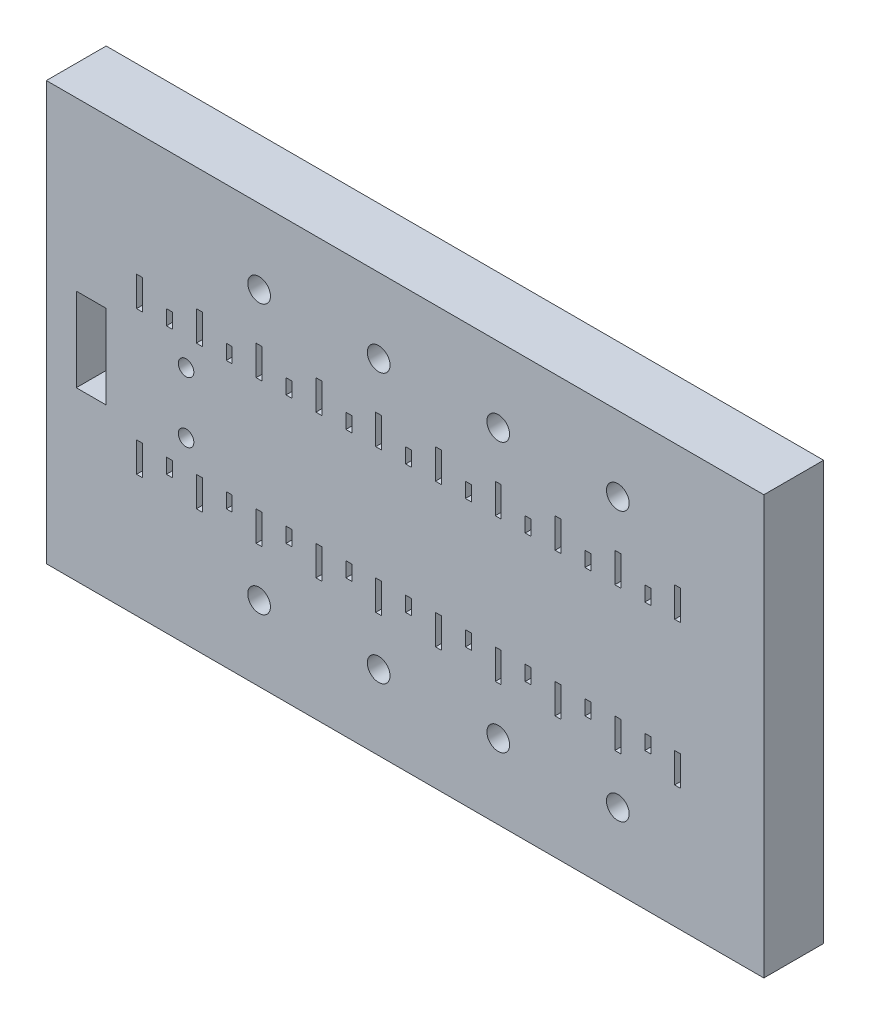
SolidWorks part; units mm, degrees
ref_plane "Front Plane" through (0, 0, 0) normal (0, 0, 1) x (1, 0, 0)
ref_plane "Top Plane" through (0, 0, 0) normal (0, 1, 0) x (1, 0, 0)
ref_plane "Right Plane" through (0, 0, 0) normal (1, 0, 0) x (0, 0, -1)
sketch "Sketch1" plane through (0, 0, 0) normal (0, 0, 1) x (1, 0, 0)
  line L1 (60, -35) -> (-60, -35)
  line L2 (60, -35) -> (60, 35)
  line L3 (60, 35) -> (-60, 35)
  line L4 (-60, -35) -> (-60, 35)
  line L5 (60, -35) -> (-60, 35) construction
  line L6 (60, 35) -> (-60, -35) construction
  point P0 (0, 0)
  dimension "D1" = 120
  dimension "D2" = 70
extrude "Boss-Extrude1" add sketch "Sketch1" along normal blind 10
sketch "Sketch2" plane through (0, 0, 10) normal (0, 0, 1) x (1, 0, 0)
  line L0 (-60, 35) -> (-60, -35)
  line L2 (-60, 0) -> (-52.5, 0)
  line L3 (-55, 7) -> (-50, 7)
  line L4 (-55, 7) -> (-55, -7)
  line L5 (-55, -7) -> (-50, -7)
  line L6 (-50, 7) -> (-50, -7)
  line L7 (-55, 7) -> (-50, -7) construction
  line L8 (-55, -7) -> (-50, 7) construction
  point P3 (-60, 0)
  dimension "D1" = 7.5
  dimension "D2" = 5
  dimension "D3" = 14
extrude "Cut-Extrude1" cut sketch "Sketch2" against normal through all
sketch "Sketch3" plane through (0, 0, 10) normal (0, 0, 1) x (1, 0, 0)
  line L0 (-33.8418, 0) -> (-20.9058, 0)
  line L1 (-33.8418, -8.0899) -> (-33.8418, 8.0899) construction
  circle A0 centre (-36.6358, 5.08) radius 1.3
  circle A1 centre (-36.6358, -5.08) radius 1.3
extrude "Cut-Extrude2" cut sketch "Sketch3" against normal through all contours A0 | A1
sketch "Sketch4" plane through (0, 0, 10) normal (0, 0, 1) x (1, 0, 0)
  line L0 (-34.4209, -2) -> (-34.4209, -12)
  line L1 (-34.4209, -12) -> (-24.4209, -12)
  line L3 (-34.9209, -9.5) -> (-33.9209, -9.5)
  line L4 (-34.9209, -9.5) -> (-34.9209, -14.5)
  line L5 (-34.9209, -14.5) -> (-33.9209, -14.5)
  line L6 (-33.9209, -9.5) -> (-33.9209, -14.5)
  line L7 (-34.9209, -9.5) -> (-33.9209, -14.5) construction
  line L8 (-34.9209, -14.5) -> (-33.9209, -9.5) construction
  line L14 (-29.9127, -12) -> (-28.9127, -12)
  line L15 (-29.4127, -12) -> (-29.4127, -9.5)
  line L17 (-29.9127, -12) -> (-29.9127, -9.5)
  line L18 (-29.9127, -9.5) -> (-28.9127, -9.5)
  line L19 (-28.9127, -12) -> (-28.9127, -9.5)
  line L20 (-29.9127, -12) -> (-28.9127, -9.5) construction
  line L21 (-29.9127, -9.5) -> (-28.9127, -12) construction
  line L22 (-24.9209, -9.5) -> (-24.9209, -14.5)
  line L23 (-24.9209, -14.5) -> (-23.9209, -14.5)
  line L24 (-23.9209, -9.5) -> (-23.9209, -14.5)
  line L25 (-19.9127, -12) -> (-18.9127, -12)
  line L27 (-19.9127, -12) -> (-19.9127, -9.5)
  line L28 (-18.9127, -12) -> (-18.9127, -9.5)
  line L29 (-24.9209, -9.5) -> (-23.9209, -14.5) construction
  line L30 (-24.9209, -14.5) -> (-23.9209, -9.5) construction
  line L31 (-19.9127, -12) -> (-18.9127, -9.5) construction
  line L32 (-19.9127, -9.5) -> (-18.9127, -12) construction
  line L33 (-24.9209, -9.5) -> (-23.9209, -9.5)
  line L34 (-19.9127, -9.5) -> (-18.9127, -9.5)
  line L36 (-14.9209, -9.5) -> (-14.9209, -14.5)
  line L37 (-14.9209, -14.5) -> (-13.9209, -14.5)
  line L38 (-13.9209, -9.5) -> (-13.9209, -14.5)
  line L39 (-9.9127, -12) -> (-8.9127, -12)
  line L41 (-9.9127, -12) -> (-9.9127, -9.5)
  line L42 (-8.9127, -12) -> (-8.9127, -9.5)
  line L43 (-14.9209, -9.5) -> (-13.9209, -14.5) construction
  line L44 (-14.9209, -14.5) -> (-13.9209, -9.5) construction
  line L45 (-9.9127, -12) -> (-8.9127, -9.5) construction
  line L46 (-9.9127, -9.5) -> (-8.9127, -12) construction
  line L47 (-14.9209, -9.5) -> (-13.9209, -9.5)
  line L48 (-9.9127, -9.5) -> (-8.9127, -9.5)
  line L50 (-4.9209, -9.5) -> (-4.9209, -14.5)
  line L51 (-4.9209, -14.5) -> (-3.9209, -14.5)
  line L52 (-3.9209, -9.5) -> (-3.9209, -14.5)
  line L53 (0.0873, -12) -> (1.0873, -12)
  line L55 (0.0873, -12) -> (0.0873, -9.5)
  line L56 (1.0873, -12) -> (1.0873, -9.5)
  line L57 (-4.9209, -9.5) -> (-3.9209, -14.5) construction
  line L58 (-4.9209, -14.5) -> (-3.9209, -9.5) construction
  line L59 (0.0873, -12) -> (1.0873, -9.5) construction
  line L60 (0.0873, -9.5) -> (1.0873, -12) construction
  line L61 (-4.9209, -9.5) -> (-3.9209, -9.5)
  line L62 (0.0873, -9.5) -> (1.0873, -9.5)
  line L64 (5.0791, -9.5) -> (5.0791, -14.5)
  line L65 (5.0791, -14.5) -> (6.0791, -14.5)
  line L66 (6.0791, -9.5) -> (6.0791, -14.5)
  line L67 (10.0873, -12) -> (11.0873, -12)
  line L69 (10.0873, -12) -> (10.0873, -9.5)
  line L70 (11.0873, -12) -> (11.0873, -9.5)
  line L71 (5.0791, -9.5) -> (6.0791, -14.5) construction
  line L72 (5.0791, -14.5) -> (6.0791, -9.5) construction
  line L73 (10.0873, -12) -> (11.0873, -9.5) construction
  line L74 (10.0873, -9.5) -> (11.0873, -12) construction
  line L75 (5.0791, -9.5) -> (6.0791, -9.5)
  line L76 (10.0873, -9.5) -> (11.0873, -9.5)
  line L78 (15.0791, -9.5) -> (15.0791, -14.5)
  line L79 (15.0791, -14.5) -> (16.0791, -14.5)
  line L80 (16.0791, -9.5) -> (16.0791, -14.5)
  line L81 (20.0873, -12) -> (21.0873, -12)
  line L83 (20.0873, -12) -> (20.0873, -9.5)
  line L84 (21.0873, -12) -> (21.0873, -9.5)
  line L85 (15.0791, -9.5) -> (16.0791, -14.5) construction
  line L86 (15.0791, -14.5) -> (16.0791, -9.5) construction
  line L87 (20.0873, -12) -> (21.0873, -9.5) construction
  line L88 (20.0873, -9.5) -> (21.0873, -12) construction
  line L89 (15.0791, -9.5) -> (16.0791, -9.5)
  line L90 (20.0873, -9.5) -> (21.0873, -9.5)
  line L92 (25.0791, -9.5) -> (25.0791, -14.5)
  line L93 (25.0791, -14.5) -> (26.0791, -14.5)
  line L94 (26.0791, -9.5) -> (26.0791, -14.5)
  line L95 (30.0873, -12) -> (31.0873, -12)
  line L97 (30.0873, -12) -> (30.0873, -9.5)
  line L98 (31.0873, -12) -> (31.0873, -9.5)
  line L99 (25.0791, -9.5) -> (26.0791, -14.5) construction
  line L100 (25.0791, -14.5) -> (26.0791, -9.5) construction
  line L101 (30.0873, -12) -> (31.0873, -9.5) construction
  line L102 (30.0873, -9.5) -> (31.0873, -12) construction
  line L103 (25.0791, -9.5) -> (26.0791, -9.5)
  line L104 (30.0873, -9.5) -> (31.0873, -9.5)
  line L106 (35.0791, -9.5) -> (35.0791, -14.5)
  line L107 (35.0791, -14.5) -> (36.0791, -14.5)
  line L108 (36.0791, -9.5) -> (36.0791, -14.5)
  line L109 (40.0873, -12) -> (41.0873, -12)
  line L111 (40.0873, -12) -> (40.0873, -9.5)
  line L112 (41.0873, -12) -> (41.0873, -9.5)
  line L113 (35.0791, -9.5) -> (36.0791, -14.5) construction
  line L114 (35.0791, -14.5) -> (36.0791, -9.5) construction
  line L115 (40.0873, -12) -> (41.0873, -9.5) construction
  line L116 (40.0873, -9.5) -> (41.0873, -12) construction
  line L117 (35.0791, -9.5) -> (36.0791, -9.5)
  line L118 (40.0873, -9.5) -> (41.0873, -9.5)
  line L120 (45.0791, -9.5) -> (45.0791, -14.5)
  line L121 (45.0791, -14.5) -> (46.0791, -14.5)
  line L122 (46.0791, -9.5) -> (46.0791, -14.5)
  line L127 (45.0791, -9.5) -> (46.0791, -14.5) construction
  line L128 (45.0791, -14.5) -> (46.0791, -9.5) construction
  line L131 (45.0791, -9.5) -> (46.0791, -9.5)
  line L133 (0, 0) -> (-11.6549, 0)
  line L136 (-43.9209, -14.5) -> (-44.9209, -9.5) construction
  line L137 (45.0791, 14.5) -> (46.0791, 9.5) construction
  line L138 (45.0791, 9.5) -> (46.0791, 14.5) construction
  line L139 (40.0873, 9.5) -> (41.0873, 12) construction
  line L140 (40.0873, 12) -> (41.0873, 9.5) construction
  line L141 (35.0791, 14.5) -> (36.0791, 9.5) construction
  line L142 (35.0791, 9.5) -> (36.0791, 14.5) construction
  line L143 (30.0873, 9.5) -> (31.0873, 12) construction
  line L144 (30.0873, 12) -> (31.0873, 9.5) construction
  line L145 (25.0791, 14.5) -> (26.0791, 9.5) construction
  line L146 (25.0791, 9.5) -> (26.0791, 14.5) construction
  line L147 (20.0873, 9.5) -> (21.0873, 12) construction
  line L148 (20.0873, 12) -> (21.0873, 9.5) construction
  line L149 (15.0791, 14.5) -> (16.0791, 9.5) construction
  line L150 (15.0791, 9.5) -> (16.0791, 14.5) construction
  line L151 (10.0873, 9.5) -> (11.0873, 12) construction
  line L152 (10.0873, 12) -> (11.0873, 9.5) construction
  line L153 (5.0791, 14.5) -> (6.0791, 9.5) construction
  line L154 (5.0791, 9.5) -> (6.0791, 14.5) construction
  line L155 (0.0873, 9.5) -> (1.0873, 12) construction
  line L156 (0.0873, 12) -> (1.0873, 9.5) construction
  line L157 (-4.9209, 14.5) -> (-3.9209, 9.5) construction
  line L158 (-4.9209, 9.5) -> (-3.9209, 14.5) construction
  line L159 (-9.9127, 9.5) -> (-8.9127, 12) construction
  line L160 (-9.9127, 12) -> (-8.9127, 9.5) construction
  line L161 (-14.9209, 14.5) -> (-13.9209, 9.5) construction
  line L162 (-14.9209, 9.5) -> (-13.9209, 14.5) construction
  line L163 (-19.9127, 9.5) -> (-18.9127, 12) construction
  line L164 (-19.9127, 12) -> (-18.9127, 9.5) construction
  line L165 (-24.9209, 14.5) -> (-23.9209, 9.5) construction
  line L166 (-24.9209, 9.5) -> (-23.9209, 14.5) construction
  line L167 (-29.9127, 9.5) -> (-28.9127, 12) construction
  line L168 (-29.9127, 12) -> (-28.9127, 9.5) construction
  line L169 (-34.9209, 14.5) -> (-33.9209, 9.5) construction
  line L170 (-34.9209, 9.5) -> (-33.9209, 14.5) construction
  line L172 (45.0791, 9.5) -> (46.0791, 9.5)
  line L175 (-43.9209, -9.5) -> (-44.9209, -14.5) construction
  line L177 (46.0791, 9.5) -> (46.0791, 14.5)
  line L178 (45.0791, 14.5) -> (46.0791, 14.5)
  line L179 (45.0791, 9.5) -> (45.0791, 14.5)
  line L180 (-38.9291, -9.5) -> (-39.9291, -12) construction
  line L181 (40.0873, 9.5) -> (41.0873, 9.5)
  line L182 (35.0791, 9.5) -> (36.0791, 9.5)
  line L183 (41.0873, 12) -> (41.0873, 9.5)
  line L184 (40.0873, 12) -> (40.0873, 9.5)
  line L186 (40.0873, 12) -> (41.0873, 12)
  line L187 (36.0791, 9.5) -> (36.0791, 14.5)
  line L188 (35.0791, 14.5) -> (36.0791, 14.5)
  line L189 (35.0791, 9.5) -> (35.0791, 14.5)
  line L191 (30.0873, 9.5) -> (31.0873, 9.5)
  line L192 (25.0791, 9.5) -> (26.0791, 9.5)
  line L193 (31.0873, 12) -> (31.0873, 9.5)
  line L194 (30.0873, 12) -> (30.0873, 9.5)
  line L196 (30.0873, 12) -> (31.0873, 12)
  line L197 (26.0791, 9.5) -> (26.0791, 14.5)
  line L198 (25.0791, 14.5) -> (26.0791, 14.5)
  line L199 (25.0791, 9.5) -> (25.0791, 14.5)
  line L201 (20.0873, 9.5) -> (21.0873, 9.5)
  line L202 (15.0791, 9.5) -> (16.0791, 9.5)
  line L203 (21.0873, 12) -> (21.0873, 9.5)
  line L204 (20.0873, 12) -> (20.0873, 9.5)
  line L206 (20.0873, 12) -> (21.0873, 12)
  line L207 (16.0791, 9.5) -> (16.0791, 14.5)
  line L208 (15.0791, 14.5) -> (16.0791, 14.5)
  line L209 (15.0791, 9.5) -> (15.0791, 14.5)
  line L211 (10.0873, 9.5) -> (11.0873, 9.5)
  line L212 (5.0791, 9.5) -> (6.0791, 9.5)
  line L213 (11.0873, 12) -> (11.0873, 9.5)
  line L214 (10.0873, 12) -> (10.0873, 9.5)
  line L216 (10.0873, 12) -> (11.0873, 12)
  line L217 (6.0791, 9.5) -> (6.0791, 14.5)
  line L218 (5.0791, 14.5) -> (6.0791, 14.5)
  line L219 (5.0791, 9.5) -> (5.0791, 14.5)
  line L221 (0.0873, 9.5) -> (1.0873, 9.5)
  line L222 (-4.9209, 9.5) -> (-3.9209, 9.5)
  line L223 (1.0873, 12) -> (1.0873, 9.5)
  line L224 (0.0873, 12) -> (0.0873, 9.5)
  line L226 (0.0873, 12) -> (1.0873, 12)
  line L227 (-3.9209, 9.5) -> (-3.9209, 14.5)
  line L228 (-4.9209, 14.5) -> (-3.9209, 14.5)
  line L229 (-4.9209, 9.5) -> (-4.9209, 14.5)
  line L231 (-9.9127, 9.5) -> (-8.9127, 9.5)
  line L232 (-14.9209, 9.5) -> (-13.9209, 9.5)
  line L233 (-8.9127, 12) -> (-8.9127, 9.5)
  line L234 (-9.9127, 12) -> (-9.9127, 9.5)
  line L236 (-9.9127, 12) -> (-8.9127, 12)
  line L237 (-13.9209, 9.5) -> (-13.9209, 14.5)
  line L238 (-14.9209, 14.5) -> (-13.9209, 14.5)
  line L239 (-14.9209, 9.5) -> (-14.9209, 14.5)
  line L241 (-19.9127, 9.5) -> (-18.9127, 9.5)
  line L242 (-24.9209, 9.5) -> (-23.9209, 9.5)
  line L243 (-18.9127, 12) -> (-18.9127, 9.5)
  line L244 (-19.9127, 12) -> (-19.9127, 9.5)
  line L246 (-19.9127, 12) -> (-18.9127, 12)
  line L247 (-23.9209, 9.5) -> (-23.9209, 14.5)
  line L248 (-24.9209, 14.5) -> (-23.9209, 14.5)
  line L249 (-24.9209, 9.5) -> (-24.9209, 14.5)
  line L250 (-28.9127, 12) -> (-28.9127, 9.5)
  line L251 (-29.9127, 9.5) -> (-28.9127, 9.5)
  line L252 (-29.9127, 12) -> (-29.9127, 9.5)
  line L254 (-29.9127, 12) -> (-28.9127, 12)
  line L256 (-33.9209, 9.5) -> (-33.9209, 14.5)
  line L257 (-34.9209, 14.5) -> (-33.9209, 14.5)
  line L258 (-34.9209, 9.5) -> (-34.9209, 14.5)
  line L259 (-34.9209, 9.5) -> (-33.9209, 9.5)
  line L261 (-34.4209, 2) -> (-34.4209, 12)
  line L262 (45.5791, -12) -> (55.5791, -12) [skipped]
  line L263 (50.0873, -12) -> (51.0873, -12) [skipped]
  line L264 (50.5873, -12) -> (50.5873, -9.5) [skipped]
  line L265 (50.0873, -12) -> (50.0873, -9.5) [skipped]
  line L266 (51.0873, -12) -> (51.0873, -9.5) [skipped]
  line L267 (50.0873, -9.5) -> (51.0873, -9.5) [skipped]
  line L268 (50.0873, -12) -> (51.0873, -9.5) construction
  line L269 (50.0873, -9.5) -> (51.0873, -12) construction
  line L270 (-38.9291, -12) -> (-39.9291, -9.5) construction
  line L271 (-43.9209, -9.5) -> (-44.9209, -9.5)
  line L272 (-44.9209, -9.5) -> (-44.9209, -14.5)
  line L273 (-43.9209, -14.5) -> (-44.9209, -14.5)
  line L274 (-43.9209, -9.5) -> (-43.9209, -14.5)
  line L275 (-39.9291, -12) -> (-39.9291, -9.5)
  line L276 (-38.9291, -9.5) -> (-39.9291, -9.5)
  line L277 (-38.9291, -12) -> (-38.9291, -9.5)
  line L279 (-38.9291, -12) -> (-39.9291, -12)
  line L280 (-38.9291, 12) -> (-39.9291, 9.5) construction
  line L281 (-38.9291, 9.5) -> (-39.9291, 12) construction
  line L282 (-43.9209, 9.5) -> (-44.9209, 14.5) construction
  line L283 (-43.9209, 14.5) -> (-44.9209, 9.5) construction
  line L284 (-38.9291, 12) -> (-39.9291, 12)
  line L286 (-38.9291, 12) -> (-38.9291, 9.5)
  line L287 (-38.9291, 9.5) -> (-39.9291, 9.5)
  line L288 (-39.9291, 12) -> (-39.9291, 9.5)
  line L289 (-43.9209, 9.5) -> (-43.9209, 14.5)
  line L290 (-43.9209, 14.5) -> (-44.9209, 14.5)
  line L291 (-44.9209, 9.5) -> (-44.9209, 14.5)
  line L292 (-43.9209, 9.5) -> (-44.9209, 9.5)
  line L293 (-24.4209, -12) -> (-14.4209, -12) [skipped]
  line L294 (-14.4209, -12) -> (-4.4209, -12) [skipped]
  line L295 (-4.4209, -12) -> (5.5791, -12) [skipped]
  line L296 (5.5791, -12) -> (15.5791, -12) [skipped]
  line L297 (15.5791, -12) -> (25.5791, -12) [skipped]
  line L298 (25.5791, -12) -> (35.5791, -12) [skipped]
  line L299 (35.5791, -12) -> (45.5791, -12) [skipped]
  line L300 (-19.4127, -12) -> (-19.4127, -9.5) [skipped]
  line L301 (-9.4127, -12) -> (-9.4127, -9.5) [skipped]
  line L302 (0.5873, -12) -> (0.5873, -9.5) [skipped]
  line L303 (10.5873, -12) -> (10.5873, -9.5) [skipped]
  line L304 (20.5873, -12) -> (20.5873, -9.5) [skipped]
  line L305 (30.5873, -12) -> (30.5873, -9.5) [skipped]
  line L306 (40.5873, -12) -> (40.5873, -9.5) [skipped]
  point P6 (-29.4127, -10.75)
  point P11 (-29.4209, -12)
  point P17 (50.5791, -12)
  point P22 (-19.4127, -10.75)
  point P27 (-19.4209, -12)
  point P31 (50.5873, -10.75)
  point P36 (-9.4127, -10.75)
  point P41 (-9.4209, -12)
  point P50 (0.5873, -10.75)
  point P55 (0.5791, -12)
  point P64 (10.5873, -10.75)
  point P69 (10.5791, -12)
  point P78 (20.5873, -10.75)
  point P83 (20.5791, -12)
  point P92 (30.5873, -10.75)
  point P97 (30.5791, -12)
  point P106 (40.5873, -10.75)
  point P111 (40.5791, -12)
  point P128 (-39.4209, -12)
  point P194 (-39.4291, -10.75)
  point P225 (40.5791, 12)
  point P226 (40.5873, 10.75)
  point P227 (30.5791, 12)
  point P228 (30.5873, 10.75)
  point P229 (20.5791, 12)
  point P230 (20.5873, 10.75)
  point P231 (10.5791, 12)
  point P232 (10.5873, 10.75)
  point P233 (0.5791, 12)
  point P234 (0.5873, 10.75)
  point P235 (-9.4209, 12)
  point P236 (-9.4127, 10.75)
  point P237 (-19.4209, 12)
  point P238 (-19.4127, 10.75)
  point P239 (-29.4209, 12)
  point P240 (-29.4127, 10.75)
  point P263 (-39.4291, 10.75)
  point P264 (-39.4209, 12)
  dimension "D1" = 1
  dimension "D2" = 10
  dimension "D3" = 10
  dimension "D4" = 5
  dimension "D5" = 1
  dimension "D6" = 2.5
  dimension "D7" = 9
sketch "Sketch5" plane through (0, 0, 10) normal (0, 0, 1) x (1, 0, 0)
  line L0 (-23.9209, -14.5) -> (-24.9209, -14.5)
  line L1 (-24.4209, -14.5) -> (-24.4209, -22.5)
  line L2 (0, 0) -> (-11.6549, 0)
  circle A0 centre (-24.4209, -22.5) radius 1.9
  circle A1 centre (-14.4209, -22.5) radius 1.9
  circle A2 centre (-4.4209, -22.5) radius 1.9
  circle A3 centre (5.5791, -22.5) radius 1.9
  circle A4 centre (15.5791, -22.5) radius 1.9
  circle A5 centre (25.5791, -22.5) radius 1.9
  circle A6 centre (35.5791, -22.5) radius 1.9
  circle A7 centre (45.5791, -22.5) radius 1.9
  circle A8 centre (45.5791, 22.5) radius 1.9
  circle A9 centre (35.5791, 22.5) radius 1.9
  circle A10 centre (25.5791, 22.5) radius 1.9
  circle A11 centre (15.5791, 22.5) radius 1.9
  circle A12 centre (5.5791, 22.5) radius 1.9
  circle A13 centre (-4.4209, 22.5) radius 1.9
  circle A14 centre (-14.4209, 22.5) radius 1.9
  circle A15 centre (-24.4209, 22.5) radius 1.9
  dimension "D2" = 3.8
  dimension "D1" = 8
  dimension "D3" = 8
extrude "Cut-Extrude3" cut sketch "Sketch5" against normal through all
sketch "Sketch7" plane through (0, 0, 0) normal (0, 0, -1) x (-1, 0, 0)
  line L0 (0, 0) -> (8.0828, 0)
  line L1 (19.6866, -22.5) -> (22.0538, -26.6)
  line L2 (22.0538, -26.6) -> (26.788, -26.6)
  line L3 (26.788, -26.6) -> (29.1552, -22.5)
  line L4 (29.1552, -22.5) -> (26.788, -18.4)
  line L5 (26.788, -18.4) -> (22.0538, -18.4)
  line L6 (22.0538, -18.4) -> (19.6866, -22.5)
  line L7 (0, 0) -> (11.6549, 0) construction
  line L8 (6.788, -26.6) -> (9.1552, -22.5)
  line L9 (2.0538, -26.6) -> (6.788, -26.6)
  line L10 (-0.3134, -22.5) -> (2.0538, -26.6)
  line L11 (2.0538, -18.4) -> (-0.3134, -22.5)
  line L12 (6.788, -18.4) -> (2.0538, -18.4)
  line L13 (9.1552, -22.5) -> (6.788, -18.4)
  line L14 (-13.212, -26.6) -> (-10.8448, -22.5)
  line L15 (-17.9462, -26.6) -> (-13.212, -26.6)
  line L16 (-20.3134, -22.5) -> (-17.9462, -26.6)
  line L17 (-17.9462, -18.4) -> (-20.3134, -22.5)
  line L18 (-13.212, -18.4) -> (-17.9462, -18.4)
  line L19 (-10.8448, -22.5) -> (-13.212, -18.4)
  line L20 (-33.212, -26.6) -> (-30.8448, -22.5)
  line L21 (-37.9462, -26.6) -> (-33.212, -26.6)
  line L22 (-40.3134, -22.5) -> (-37.9462, -26.6)
  line L23 (-37.9462, -18.4) -> (-40.3134, -22.5)
  line L24 (-33.212, -18.4) -> (-37.9462, -18.4)
  line L25 (-30.8448, -22.5) -> (-33.212, -18.4)
  line L26 (6.788, 18.4) -> (9.1552, 22.5)
  line L27 (2.0538, 18.4) -> (6.788, 18.4)
  line L28 (-0.3134, 22.5) -> (2.0538, 18.4)
  line L29 (2.0538, 26.6) -> (-0.3134, 22.5)
  line L30 (6.788, 26.6) -> (2.0538, 26.6)
  line L31 (9.1552, 22.5) -> (6.788, 26.6)
  line L32 (-13.212, 18.4) -> (-10.8448, 22.5)
  line L33 (-17.9462, 18.4) -> (-13.212, 18.4)
  line L34 (-20.3134, 22.5) -> (-17.9462, 18.4)
  line L35 (-17.9462, 26.6) -> (-20.3134, 22.5)
  line L36 (-13.212, 26.6) -> (-17.9462, 26.6)
  line L37 (-10.8448, 22.5) -> (-13.212, 26.6)
  line L38 (-33.212, 18.4) -> (-30.8448, 22.5)
  line L39 (-37.9462, 18.4) -> (-33.212, 18.4)
  line L40 (-40.3134, 22.5) -> (-37.9462, 18.4)
  line L41 (-37.9462, 26.6) -> (-40.3134, 22.5)
  line L42 (-33.212, 26.6) -> (-37.9462, 26.6)
  line L43 (-30.8448, 22.5) -> (-33.212, 26.6)
  line L44 (26.788, 18.4) -> (29.1552, 22.5)
  line L45 (22.0538, 18.4) -> (26.788, 18.4)
  line L46 (19.6866, 22.5) -> (22.0538, 18.4)
  line L47 (22.0538, 26.6) -> (19.6866, 22.5)
  line L48 (26.788, 26.6) -> (22.0538, 26.6)
  line L49 (29.1552, 22.5) -> (26.788, 26.6)
  circle A0 centre (24.4209, -22.5) radius 4.1 construction
  circle M7 centre (4.4209, -22.5) radius 1.9
  circle M8 centre (-15.5791, -22.5) radius 1.9
  circle M9 centre (-35.5791, -22.5) radius 1.9
  circle M10 centre (24.4209, -22.5) radius 1.9
  circle M21 centre (-15.5791, 22.5) radius 1.9
  circle M22 centre (4.4209, 22.5) radius 1.9
  circle M23 centre (-35.5791, 22.5) radius 1.9
  circle M24 centre (24.4209, 22.5) radius 1.9
  dimension "D1" = 8.2
  dimension "D2" = 2
extrude "Cut-Extrude4" cut sketch "Sketch7" against normal blind 7 contours L5 L6 L1 L2 L3 L4 M10 | L8 L13 L12 L11 L10 L9 M7 | L14 L19 L18 L17 L16 L15 M8 | L20 L25 L24 L23 L22 L21 M9 | L38 L43 L42 L41 L40 L39 M23 | L32 L37 L36 L35 L34 L33 M21 | L26 L31 L30 L29 L28 L27 M22 | L44 L49 L48 L47 L46 L45 M24
extrude "Cut-Extrude5" cut sketch "Sketch4" against normal blind 1
